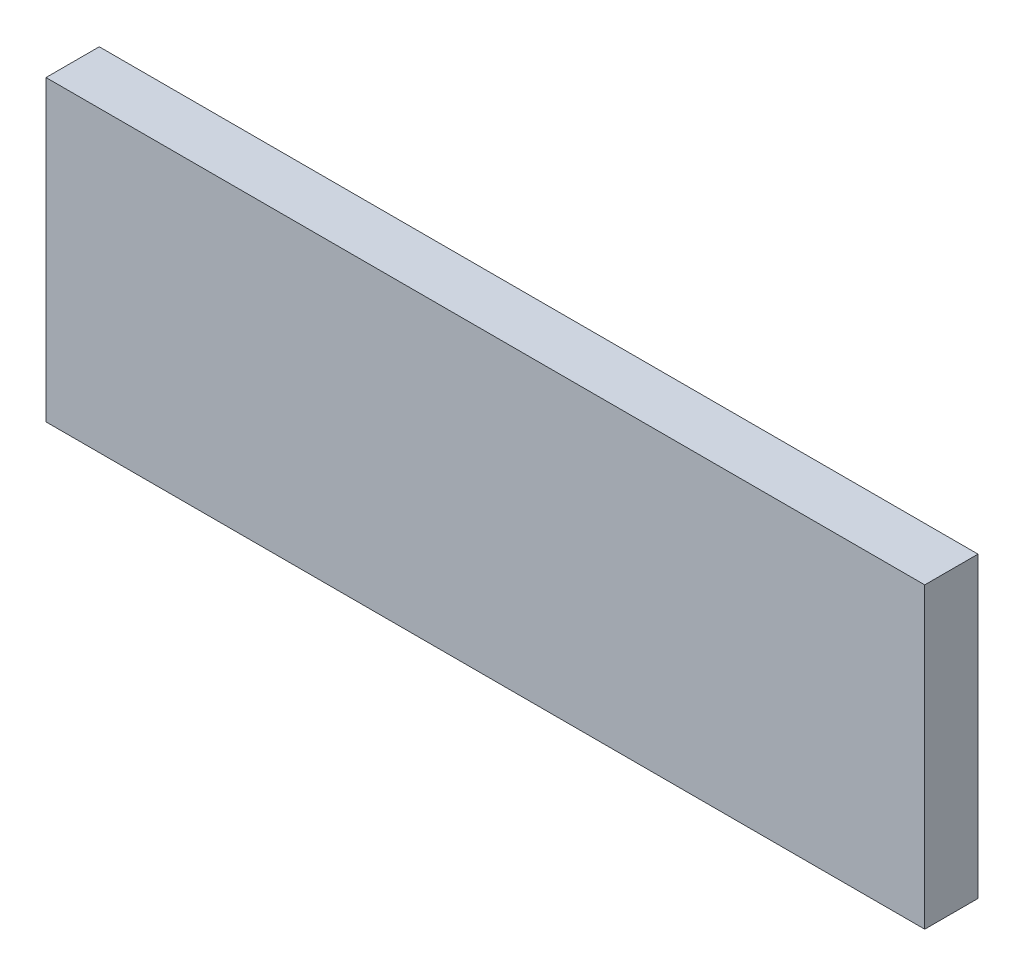
SolidWorks part; units mm, degrees
ref_plane "Front Plane" through (0, 0, 0) normal (0, 0, 1) x (1, 0, 0)
ref_plane "Top Plane" through (0, 0, 0) normal (0, 1, 0) x (1, 0, 0)
ref_plane "Right Plane" through (0, 0, 0) normal (1, 0, 0) x (0, 0, -1)
sketch "Sketch1" plane through (0, 0, 0) normal (0, 0, 1) x (1, 0, 0)
  line L0 (-82.5, 0) -> (-85.5, 0)
  line L1 (-82.5, -28) -> (82.5, -28)
  line L2 (-82.5, -28) -> (-82.5, 28)
  line L3 (-82.5, 28) -> (82.5, 28)
  line L4 (82.5, -28) -> (82.5, 28)
  line L5 (-82.5, -28) -> (82.5, 28) construction
  line L6 (-82.5, 28) -> (82.5, -28) construction
  line L7 (-85.5, 31) -> (85.5, 31) construction
  line L8 (-85.5, 31) -> (-85.5, -31) construction
  line L9 (-85.5, -31) -> (85.5, -31) construction
  line L10 (85.5, 31) -> (85.5, -31) construction
  line L11 (-85.5, 31) -> (85.5, -31) construction
  line L12 (-85.5, -31) -> (85.5, 31) construction
  line L13 (0, 28) -> (0, 31) construction
  point P0 (0, 0)
  point P6 (0, 0)
  dimension "D1" = 56
  dimension "D2" = 165
  dimension "D3" = 3
extrude "Boss-Extrude2" add sketch "Sketch1" along normal blind 10 contours L1 L4 L3 L2
